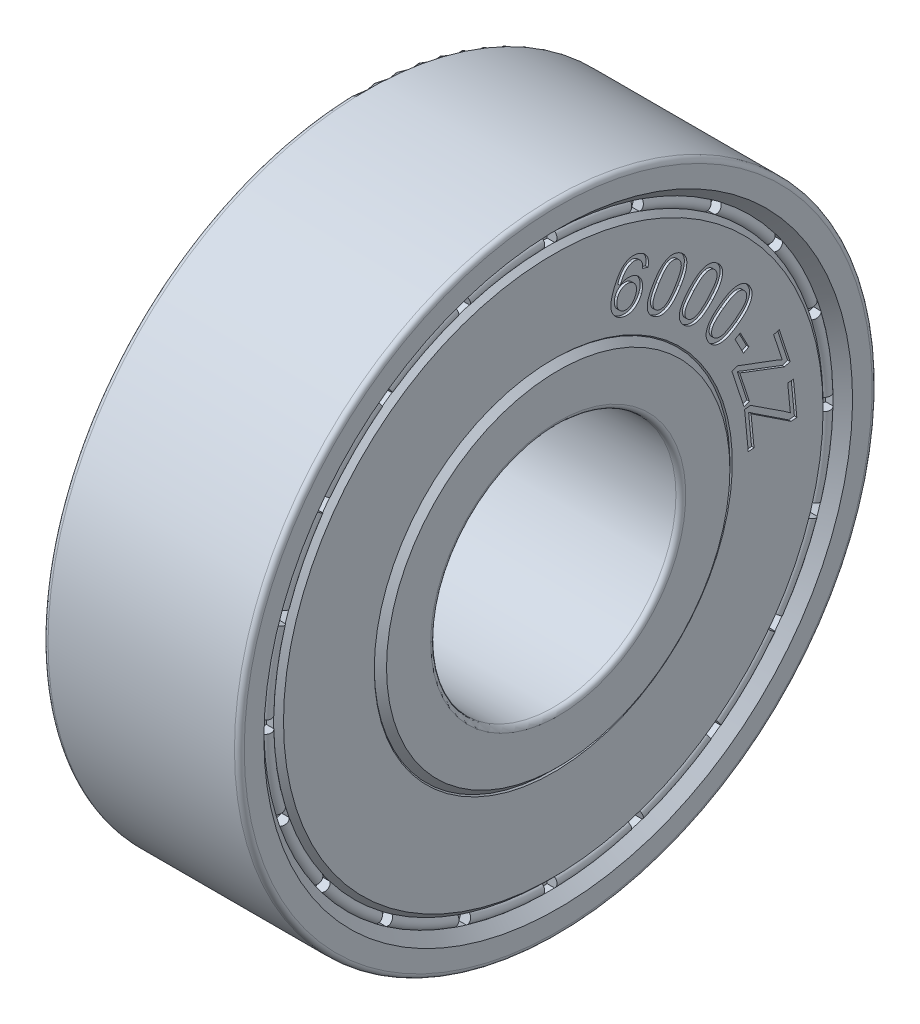
SolidWorks part; units mm, degrees
material "Простая углеродистая сталь"
ref_plane "Спереди" through (0, 0, 0) normal (0, 0, 1) x (1, 0, 0)
ref_plane "Сверху" through (0, 0, 0) normal (0, 1, 0) x (1, 0, 0)
ref_plane "Справа" through (0, 0, 0) normal (1, 0, 0) x (0, 0, -1)
sketch "Эскиз1" plane through (0, 0, 0) normal (0, 0, 1) x (1, 0, 0)
  line L0 (-17.0192, 0) -> (17.0192, 0) construction
  line L1 (-4, 5) -> (4, 5)
  line L2 (4, 5) -> (4, 7)
  line L3 (4, 13) -> (-4, 13)
  line L4 (-4, 13) -> (-4, 12)
  line L5 (-4, 7) -> (-3.75, 7.25)
  line L6 (-3.75, 7.25) -> (-3.8, 7.3)
  line L7 (-3.8, 7.3) -> (-3.8, 11)
  line L9 (-3.6, 11.6) -> (-4, 12)
  line L10 (-4, 7) -> (-4, 5)
  line L11 (0, 5) -> (0, 8.0594) construction
  line L12 (4, 7) -> (3.75, 7.25)
  line L13 (3.75, 7.25) -> (3.8, 7.3)
  line L14 (3.8, 7.3) -> (3.8, 11)
  line L16 (3.6, 11.6) -> (4, 12)
  line L17 (4, 12) -> (4, 13)
  line L18 (-3.6, 11.6) -> (-3.6, 11.2) construction
  line L19 (-3.6, 11.2) -> (-3.8, 11)
  line L20 (3.6, 11.6) -> (3.6, 11.2) construction
  line L21 (3.6, 11.2) -> (3.8, 11)
  arc A0 (-3.6, 11.6) -> (-3.6, 11.2) centre (-3.45, 11.4) ccw
  arc A1 (3.6, 11.6) -> (3.6, 11.2) centre (3.45, 11.4) cw
  point P4 (0, 0)
  point P8 (0, 5)
  dimension "D11" = 0.15
  dimension "D1" = 26
  dimension "D2" = 8
  dimension "D3" = 10
  dimension "D4" = 0.2
  dimension "D5" = 0.25
  dimension "D6" = 45
  dimension "D7" = 2
  dimension "D8" = 1
  dimension "D9" = 45
  dimension "D10" = 0.2
  dimension "D12" = 0.4
revolve "Повернуть1" add sketch "Эскиз1" angle 360 about L0
fillet "Скругление1" radius 0.2 4 edges at (-4, 0, 5) (4, 0, 5) (4, 0, 13) (-4, 0, 13)
sketch "Эскиз2" plane through (-3.8, 0, 0) normal (-1, 0, 0) x (0, 0, 1)
  line L0 (-0.25, 11.5973) -> (-0.25, 11.1972)
  line L2 (0.25, 11.1972) -> (0.25, 11.5973)
  line L3 (0, 3.5762) -> (0, 14.7417) construction
  arc A2 (0.25, 11.1972) -> (-0.25, 11.1972) centre (0, 0) ccw
  arc A3 (0.25, 11.5973) -> (-0.25, 11.5973) centre (0, 0) ccw
  circle A5 centre (0, 0) radius 11.6 construction
  circle A7 centre (0, 0) radius 11.2 construction
  dimension "D1" = 0.5
extrude "Вырез-Вытянуть1" cut sketch "Эскиз2" against normal blind 0.5
mirror "Зеркальное отражение1" about plane through (0, 0, 0) normal (1, 0, 0) of "Вырез-Вытянуть1"
pattern_circular "Круговой массив1" count 20 over 360 about axis through (0, 0, 0) along (1, 0, 0) of "Зеркальное отражение1", "Вырез-Вытянуть1"
sketch "Эскиз3" plane through (3.8, 0, 0) normal (1, 0, 0) x (0, 0, -1)
  circle A0 centre (0, 0) radius 7.9715 construction
  text T0 "6000-ZZ" font "Arial" height 2
extrude "Вырез-Вытянуть2" cut sketch "Эскиз3" against normal blind 0.1
